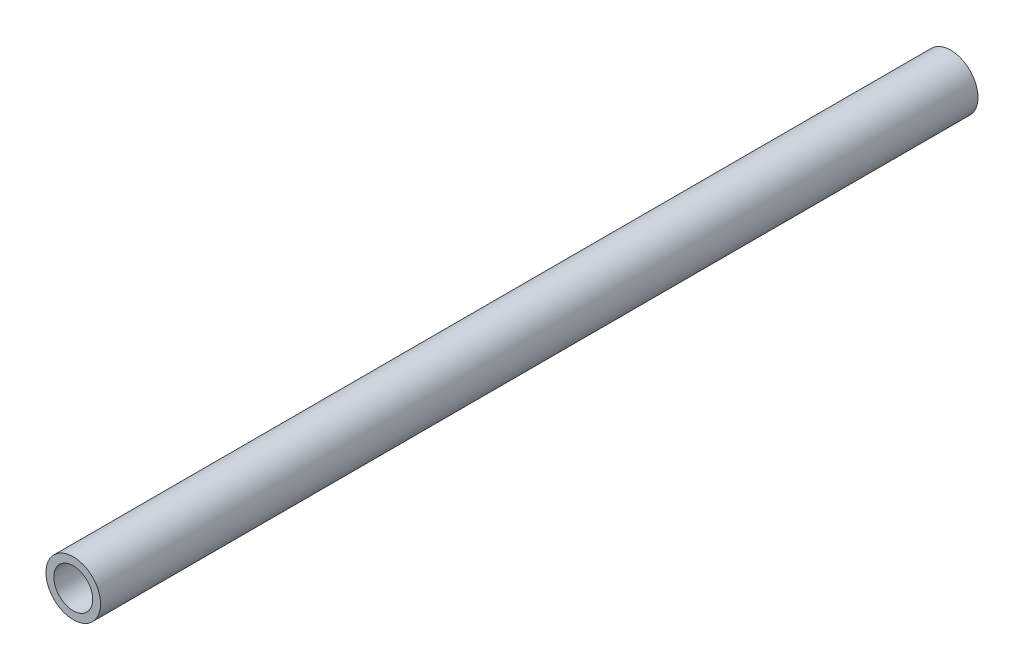
SolidWorks part; units mm, degrees
material "EM-CF"
ref_plane "Płaszczyzna przednia" through (0, 0, 0) normal (0, 0, 1) x (1, 0, 0)
ref_plane "Płaszczyzna górna" through (0, 0, 0) normal (0, 1, 0) x (1, 0, 0)
ref_plane "Płaszczyzna prawa" through (0, 0, 0) normal (1, 0, 0) x (0, 0, -1)
sketch "Szkic1" plane through (0, 0, 0) normal (0, 0, 1) x (1, 0, 0)
  circle A0 centre (0, 0) radius 5
  circle A1 centre (0, 0) radius 7
  dimension "D1" = 2
  dimension "D2" = 14
extrude "Dodanie-wyciągnięcie1" add sketch "Szkic1" along normal blind 225
